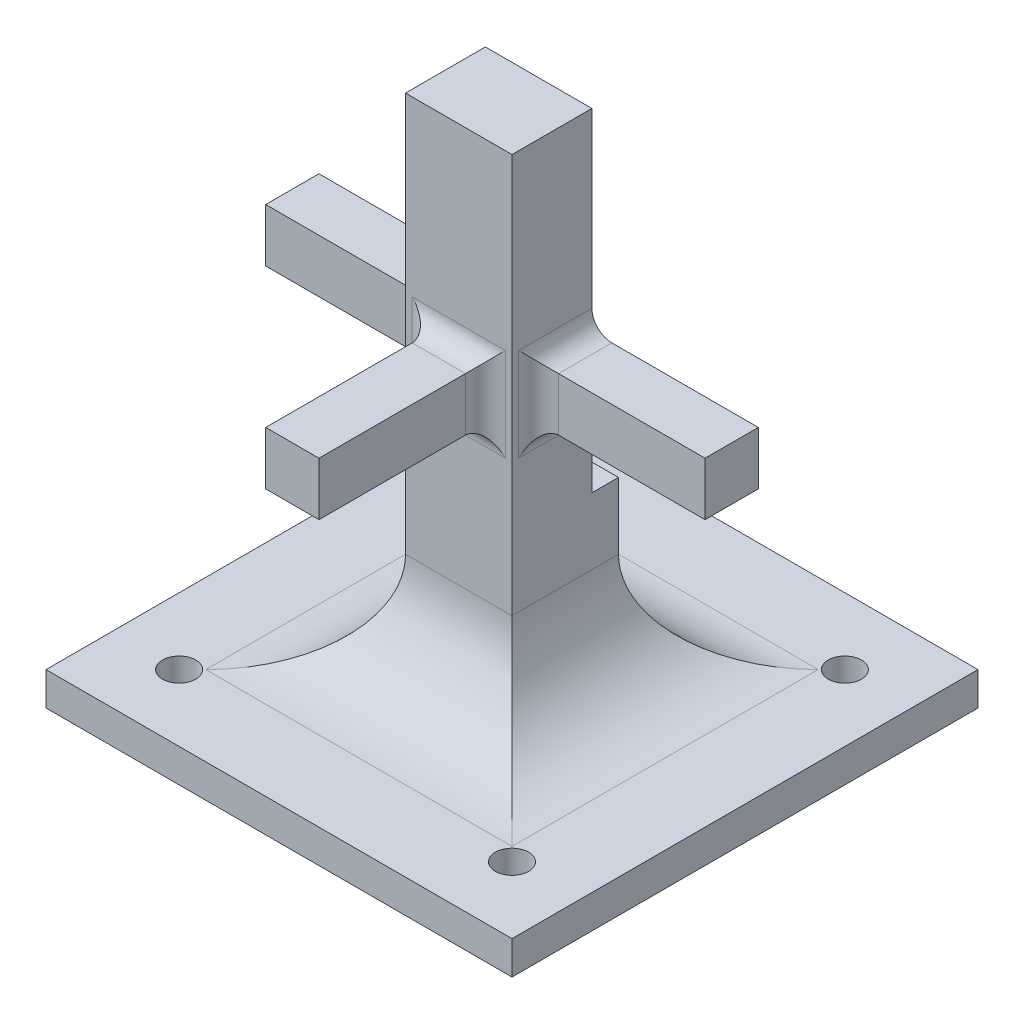
SolidWorks part; units mm, degrees
ref_plane "前视基准面" through (0, 0, 0) normal (0, 0, 1) x (1, 0, 0)
ref_plane "上视基准面" through (0, 0, 0) normal (0, 1, 0) x (1, 0, 0)
ref_plane "右视基准面" through (0, 0, 0) normal (1, 0, 0) x (0, 0, -1)
sketch "Sketch1" plane through (0, 0, 0) normal (0, 1, 0) x (1, 0, 0)
  line L1 (-35, 35) -> (35, 35)
  line L2 (-35, 35) -> (-35, -35)
  line L3 (-35, -35) -> (35, -35)
  line L4 (35, 35) -> (35, -35)
  line L5 (-35, 35) -> (35, -35) construction
  line L6 (-35, -35) -> (35, 35) construction
  point P0 (0, 0)
extrude "Boss-Extrude1" add sketch "Sketch1" along normal blind 5
sketch "Sketch2" plane through (0, 5, 0) normal (0, 1, 0) x (1, 0, 0)
  circle A0 centre (-25, 25) radius 2.5
extrude "Cut-Extrude1" cut sketch "Sketch2" against normal blind 5
sketch "Sketch3" plane through (0, 5, 0) normal (0, 1, 0) x (1, 0, 0)
  circle A0 centre (25, 25) radius 2.5
extrude "Cut-Extrude2" cut sketch "Sketch3" against normal blind 5
sketch "Sketch4" plane through (0, 5, 0) normal (0, 1, 0) x (1, 0, 0)
  circle A0 centre (-25, -25) radius 2.5
extrude "Cut-Extrude3" cut sketch "Sketch4" against normal blind 5
sketch "Sketch5" plane through (0, 5, 0) normal (0, 1, 0) x (1, 0, 0)
  circle A0 centre (25, -25) radius 2.5
extrude "Cut-Extrude4" cut sketch "Sketch5" against normal blind 5
sketch "Sketch7" plane through (0, 5, 0) normal (0, 1, 0) x (1, 0, 0)
  line L1 (-8, 8) -> (8, 8)
  line L2 (-8, 8) -> (-8, -8)
  line L3 (-8, -8) -> (8, -8)
  line L4 (8, 8) -> (8, -8)
  line L5 (-8, 8) -> (8, -8) construction
  line L6 (-8, -8) -> (8, 8) construction
  point P0 (0, 0)
extrude "Boss-Extrude2" add sketch "Sketch7" along normal blind 75
sketch "Sketch8" plane through (0, 0, 8) normal (0, 0, 1) x (1, 0, 0)
  line L1 (-4, 51) -> (4, 51)
  line L2 (-4, 51) -> (-4, 43)
  line L3 (-4, 43) -> (4, 43)
  line L4 (4, 51) -> (4, 43)
  line L5 (-4, 51) -> (4, 43) construction
  line L6 (-4, 43) -> (4, 51) construction
  point P0 (0, 47)
extrude "Boss-Extrude3" add sketch "Sketch8" along normal blind 25
sketch "Sketch9" plane through (8, 0, 0) normal (1, 0, 0) x (0, 0, -1)
  line L1 (-4, 51) -> (4, 51)
  line L2 (-4, 51) -> (-4, 43)
  line L3 (-4, 43) -> (4, 43)
  line L4 (4, 51) -> (4, 43)
  line L5 (-4, 51) -> (4, 43) construction
  line L6 (-4, 43) -> (4, 51) construction
  point P0 (0, 47)
extrude "Boss-Extrude4" add sketch "Sketch9" along normal blind 25
sketch "Sketch10" plane through (-8, 0, 0) normal (-1, 0, 0) x (0, 0, 1)
  line L1 (-4, 51) -> (4, 51)
  line L2 (-4, 51) -> (-4, 43)
  line L3 (-4, 43) -> (4, 43)
  line L4 (4, 51) -> (4, 43)
  line L5 (-4, 51) -> (4, 43) construction
  line L6 (-4, 43) -> (4, 51) construction
  point P0 (0, 47)
extrude "Boss-Extrude5" add sketch "Sketch10" along normal blind 25
sketch "Sketch11" plane through (0, 80, 0) normal (0, 1, 0) x (1, 0, 0)
  line L0 (8, -8) -> (8, 8) construction
  line L1 (-8, 8) -> (8, 8)
  line L2 (-8, 8) -> (-8, 4)
  line L3 (-8, 4) -> (8, 4)
  line L4 (8, 8) -> (8, 4)
  line L5 (-8, 8) -> (8, 4) construction
  line L6 (-8, 4) -> (8, 8) construction
  point P0 (0, 6)
extrude "Cut-Extrude5" cut sketch "Sketch11" against normal blind 50
fillet "Fillet1" radius 15 4 edges at (-8, 5, 0) (0, 5, -8) (8, 5, 0) (0, 5, 8)
fillet "Fillet2" radius 3 10 edges at (8, 51, 0) (0, 51, 8) (-8, 51, 0) (8, 47, 4) (4, 47, 8) (-4, 47, 8) (-8, 47, 4) (8, 43, 0) (-8, 43, 0) (0, 43, 8)
